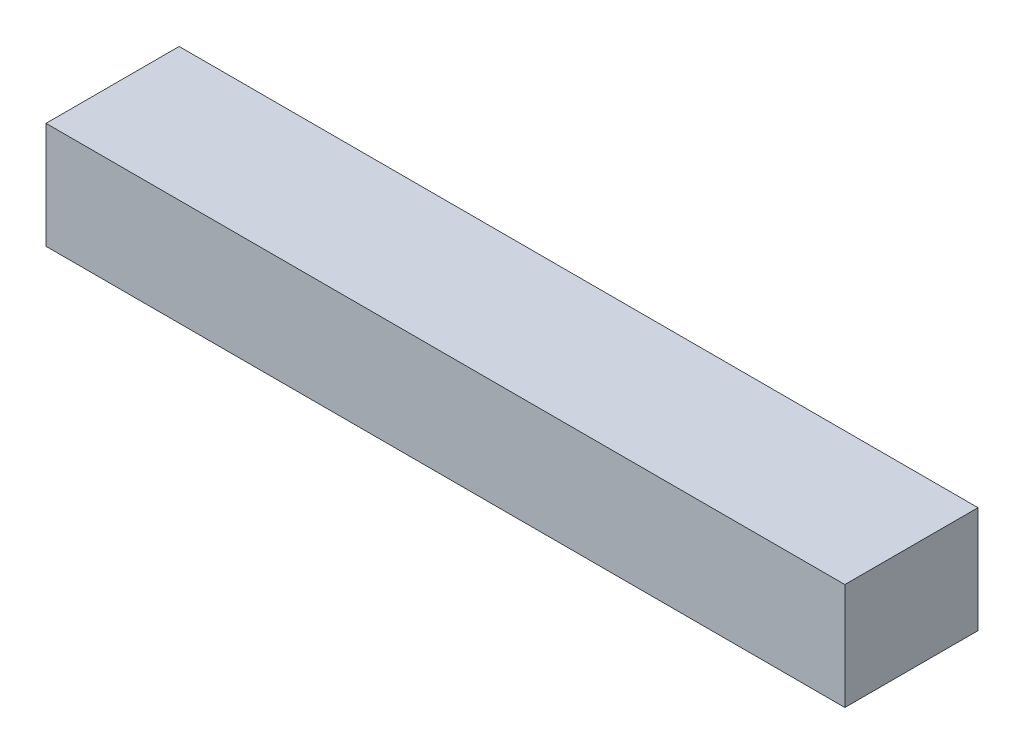
SolidWorks part; units mm, degrees
ref_plane "Alzado" through (0, 0, 0) normal (0, 0, 1) x (1, 0, 0)
ref_plane "Planta" through (0, 0, 0) normal (0, 1, 0) x (1, 0, 0)
ref_plane "Vista lateral" through (0, 0, 0) normal (1, 0, 0) x (0, 0, -1)
sketch "Croquis1" plane through (0, 0, 0) normal (0, 0, 1) x (1, 0, 0)
  line L1 (0, 0) -> (3000, 0)
  line L2 (0, 0) -> (0, -400)
  line L3 (0, -400) -> (3000, -400)
  line L4 (3000, 0) -> (3000, -400)
  dimension "D1" = 3000
  dimension "D2" = 400
extrude "Saliente-Extruir1" add sketch "Croquis1" along normal blind 500
sketch "Croquis2" plane through (0, -400, 0) normal (0, -1, 0) x (1, 0, 0)
  line L0 (3000, 250) -> (2500, 250) construction
  line L1 (3000, 500) -> (3000, 0) construction
  line L2 (0, 250) -> (500, 250) construction
  line L3 (0, 500) -> (0, 0) construction
  line L4 (1500, 0) -> (1500, 500) construction
  line L5 (0, 0) -> (3000, 0) construction
  line L6 (0, 500) -> (3000, 500) construction
  circle A0 centre (2500, 250) radius 101.6
  circle A1 centre (500, 250) radius 101.6
  circle A2 centre (1500, 250) radius 101.6
  dimension "D3" = 203.2
  dimension "D4" = 203.2
  dimension "D5" = 203.2
  dimension "D1" = 500
  dimension "D2" = 500
extrude "Saliente-Extruir2" add sketch "Croquis2" along normal blind 20
